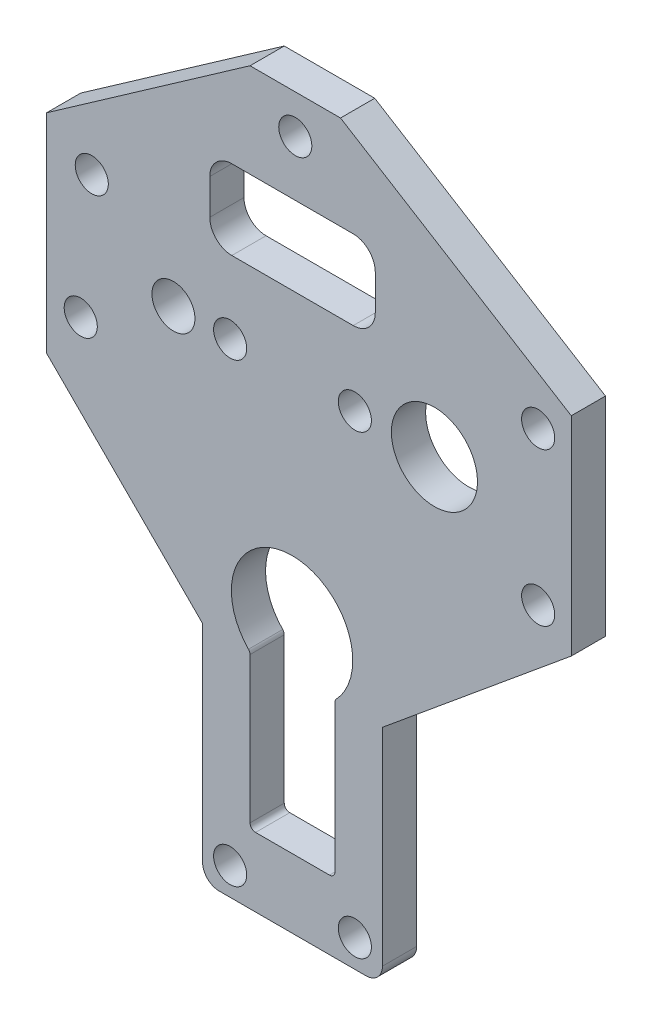
SolidWorks part; units mm, degrees
ref_plane "Front Plane" through (0, 0, 0) normal (0, 0, 1) x (1, 0, 0)
ref_plane "Top Plane" through (0, 0, 0) normal (0, 1, 0) x (1, 0, 0)
ref_plane "Right Plane" through (0, 0, 0) normal (1, 0, 0) x (0, 0, -1)
sketch "Sketch1" plane through (0, 0, 0) normal (0, 0, 1) x (1, 0, 0)
  line L0 (16.6421, -31.8921) -> (16.6421, 36.1319) construction
  line L1 (0, 0) -> (0, 18.8612)
  line L2 (0, -36.3917) -> (0, 36.3917) construction
  line L3 (0, 18.8612) -> (18.4421, 31.7745)
  line L4 (0, 18.8612) -> (99.7455, 18.8612) construction
  line L5 (0, 0) -> (14.1421, -14.1421)
  line L6 (54.86, 0) -> (-54.86, 0) construction
  line L7 (14.1421, -14.1421) -> (14.1421, -32.8921)
  line L8 (15.6421, -34.3921) -> (28.9406, -34.3921)
  line L9 (30.4406, -32.8921) -> (30.4406, -14.1434)
  line L10 (30.4406, -14.1434) -> (47.5521, 0)
  line L11 (18.4421, 31.7745) -> (26.6421, 31.7745)
  line L12 (26.6421, 31.7745) -> (47.5521, 18.8612)
  line L13 (47.5521, 18.8612) -> (47.5521, 0)
  line L14 (0, 9.4306) -> (47.5521, 9.4306) construction
  line L15 (18.4421, -14.4324) -> (18.4421, -27.6421)
  line L16 (18.9421, -28.1421) -> (25.6406, -28.1421)
  line L17 (26.1406, -27.6421) -> (26.1406, -14.3452)
  line L18 (16.6421, -31.8921) -> (27.9406, -31.8921) construction
  line L19 (18.4421, -14.2246) -> (26.1406, -14.1434) construction
  line L20 (27.9406, -31.8921) -> (27.9406, 36.1319) construction
  line L21 (16.7921, 16.0586) -> (27.7906, 16.0586)
  line L24 (16.7921, 23.2586) -> (27.7906, 23.2586)
  line L29 (14.7921, 21.2586) -> (14.7921, 18.0586)
  line L30 (29.7906, 21.2586) -> (29.7906, 18.0586)
  line L31 (22.5421, 23.8575) -> (22.5421, 31.7745) construction
  line L32 (44.5521, 2.5) -> (44.5521, 18.8612) construction
  circle A0 centre (4.1, 16.0586) radius 1.5
  circle A1 centre (3.1, 4.3786) radius 1.5
  circle A2 centre (11.5, 9.4306) radius 1.95
  circle A3 centre (35.1521, 9.4306) radius 3.9
  circle A4 centre (16.6421, -31.8921) radius 1.5
  circle A5 centre (27.9406, -31.8921) radius 1.5
  arc A6 (26.2747, -14.0044) -> (18.3011, -14.0844) centre (22.2499, -10.2559) ccw
  circle A7 centre (16.6421, 9.4306) radius 1.5
  circle A8 centre (27.9406, 9.4306) radius 1.5
  arc A13 (16.7921, 23.2586) -> (14.7921, 21.2586) centre (16.7921, 21.2586) ccw
  arc A14 (14.7921, 18.0586) -> (16.7921, 16.0586) centre (16.7921, 18.0586) ccw
  arc A15 (29.7906, 18.0586) -> (27.7906, 16.0586) centre (27.7906, 18.0586) cw
  arc A16 (29.7906, 21.2586) -> (27.7906, 23.2586) centre (27.7906, 21.2586) ccw
  circle A17 centre (22.5421, 28.2745) radius 1.5
  circle A18 centre (44.5521, 2.5) radius 1.5
  circle A19 centre (44.5521, 16.3612) radius 1.5
  arc A20 (28.9406, -34.3921) -> (30.4406, -32.8921) centre (28.9406, -32.8921) ccw
  arc A21 (14.1421, -32.8921) -> (15.6421, -34.3921) centre (15.6421, -32.8921) ccw
  arc A22 (26.1406, -14.3452) -> (26.2747, -14.0044) centre (26.6406, -14.3452) cw
  arc A23 (18.4421, -14.4324) -> (18.3011, -14.0844) centre (17.9421, -14.4324) ccw
  arc A24 (25.6406, -28.1421) -> (26.1406, -27.6421) centre (25.6406, -27.6421) ccw
  arc A25 (18.4421, -27.6421) -> (18.9421, -28.1421) centre (18.9421, -27.6421) ccw
  point P64 (45.2665, 18.8612)
  point P65 (42.7332, 17.1331)
  point P76 (26.1406, -28.1421)
  point P79 (18.4421, -28.1421)
  dimension "D3" = 4.1
  dimension "D5" = 11.5
  dimension "D6" = 12.4
  dimension "D10" = 2.5
  dimension "D13" = 7.6984
  dimension "D14" = 2
  dimension "D15" = 7.2
  dimension "D17" = 3.5
  dimension "D18" = 3
  dimension "D21" = 1.5
  dimension "D22" = 0.5
  dimension "D1" = 35
  dimension "D2" = 45
  dimension "D4" = 3.1
  dimension "D7" = 4.3
  dimension "D8" = 4.3
  dimension "D9" = 6.25
  dimension "D11" = 2.5
  dimension "D12" = 2.5
  dimension "D16" = 14.9984
  dimension "D19" = 2.5
  dimension "D20" = 2.5
extrude "Boss-Extrude1" add sketch "Sketch1" along normal blind 3.1
